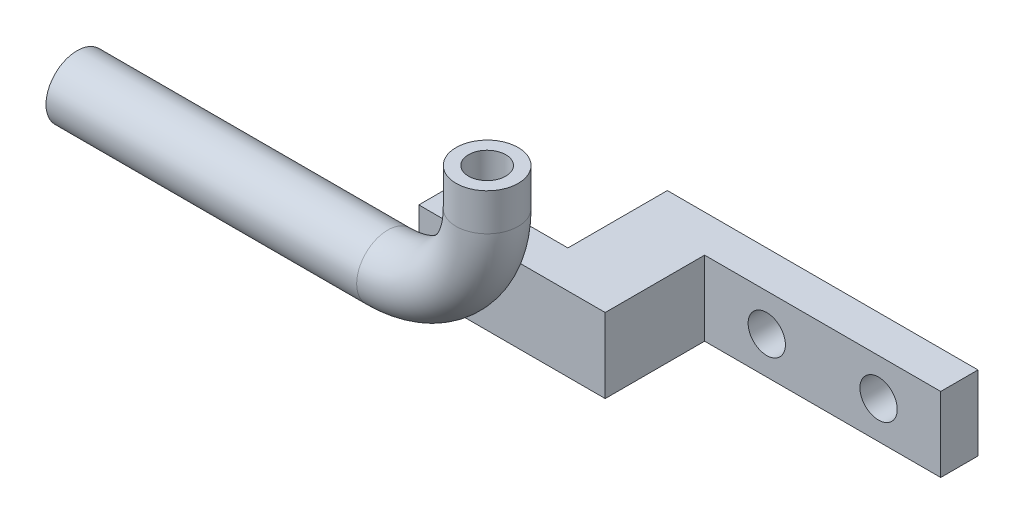
SolidWorks part; units mm, degrees
ref_plane "Front Plane" through (0, 0, 0) normal (0, 0, 1) x (1, 0, 0)
ref_plane "Top Plane" through (0, 0, 0) normal (0, 1, 0) x (1, 0, 0)
ref_plane "Right Plane" through (0, 0, 0) normal (1, 0, 0) x (0, 0, -1)
sketch "Sketch1" plane through (0, 0, 0) normal (0, 0, 1) x (1, 0, 0)
  line L0 (-60.7014, 30.563) -> (-35.7014, 30.563)
  line L1 (-27.7014, 41.563) -> (-27.7014, 38.563)
  arc A2 (-35.7014, 30.563) -> (-27.7014, 38.563) centre (-35.7014, 38.563) ccw
  dimension "D1" = 8
  dimension "D2" = 25
  dimension "D3" = 3
ref_plane "Plane1" through (0, 41.563, 0) normal (0, 1, 0) x (-1, 0, 0)
sketch "Sketch3" plane through (0, 41.563, 0) normal (0, 1, 0) x (-1, 0, 0)
  circle A0 centre (27.7014, 0) radius 1.5
  circle A1 centre (27.7014, 0) radius 2.5
  dimension "D1" = 3
  dimension "D2" = 5
sweep "Sweep1" add profiles "Sketch3" path "Sketch1"
ref_plane "Plane2" through (0, 0, -2.5) normal (0, 0, -1) x (-1, 0, 0)
sketch "Sketch4" plane through (0, 0, -2.5) normal (0, 0, -1) x (-1, 0, 0)
  line L0 (35.7014, 30.563) -> (60.7014, 30.563) construction
  line L1 (35.7014, 33.563) -> (20.7014, 33.563)
  line L2 (35.7014, 33.563) -> (35.7014, 27.563)
  line L3 (35.7014, 27.563) -> (20.7014, 27.563)
  line L4 (20.7014, 33.563) -> (20.7014, 27.563)
  line L5 (60.7014, 28.063) -> (60.7014, 33.063) construction
  dimension "D1" = 6
  dimension "D2" = 25
  dimension "D3" = 15
extrude "Boss-Extrude1" add sketch "Sketch4" along normal blind 3 separate body
sketch "Sketch5" plane through (0, 0, -2.5) normal (0, 0, 1) x (1, 0, 0)
  line L0 (-35.7014, 33.563) -> (-20.7014, 33.563) construction
  line L1 (-20.7014, 27.563) -> (-26.7014, 27.563)
  line L2 (-20.7014, 27.563) -> (-20.7014, 33.563)
  line L3 (-20.7014, 33.563) -> (-26.7014, 33.563)
  line L4 (-26.7014, 27.563) -> (-26.7014, 33.563)
extrude "Boss-Extrude2" add sketch "Sketch5" against normal blind 11
sketch "Sketch6" plane through (0, 0, -13.5) normal (0, 0, -1) x (-1, 0, 0)
  line L0 (20.7014, 27.563) -> (20.7014, 33.563) construction
  line L1 (26.7014, 33.563) -> (1.7014, 33.563)
  line L2 (26.7014, 33.563) -> (26.7014, 27.563)
  line L3 (26.7014, 27.563) -> (1.7014, 27.563)
  line L4 (1.7014, 33.563) -> (1.7014, 27.563)
  dimension "D1" = 25
extrude "Boss-Extrude3" add sketch "Sketch6" against normal blind 3
sketch "Sketch7" plane through (0, 0, -10.5) normal (0, 0, 1) x (1, 0, 0)
  line L0 (-1.7014, 30.563) -> (-20.7014, 30.563) construction
  line L1 (-1.7014, 33.563) -> (-1.7014, 27.563) construction
  line L2 (-20.7014, 27.563) -> (-20.7014, 33.563) construction
  circle A0 centre (-15.7014, 30.563) radius 1.5
  circle A1 centre (-6.7014, 30.563) radius 1.5
  dimension "D1" = 3
  dimension "D2" = 5
  dimension "D3" = 5
extrude "Cut-Extrude1" cut sketch "Sketch7" against normal through all
